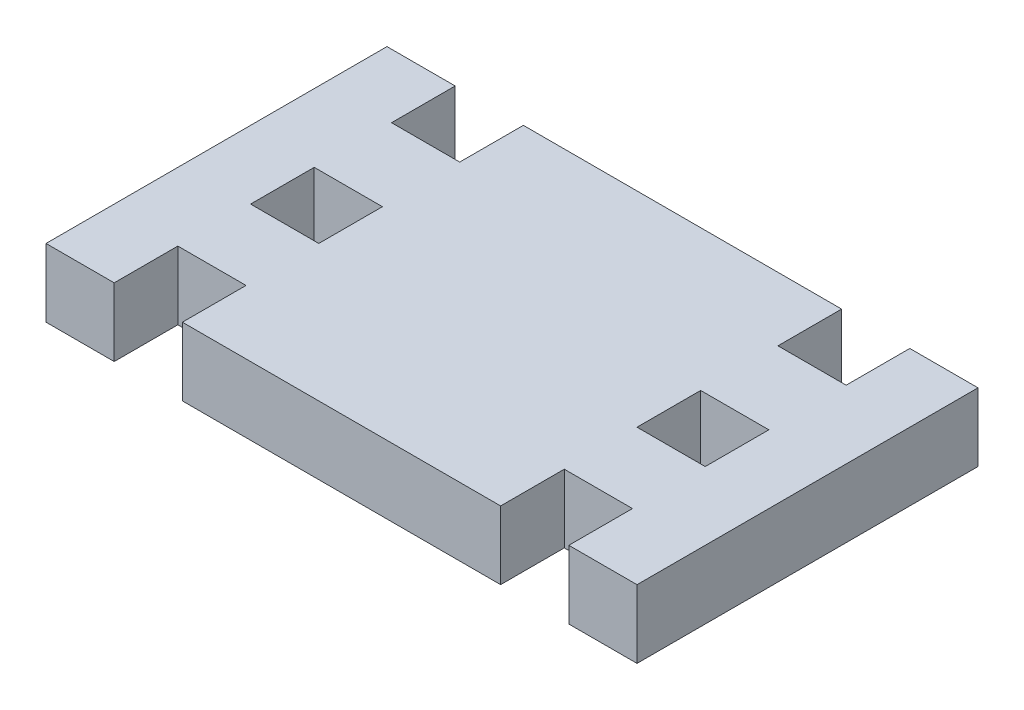
SolidWorks part; units mm, degrees
ref_plane "Front Plane" through (0, 0, 0) normal (0, 0, 1) x (1, 0, 0)
ref_plane "Top Plane" through (0, 0, 0) normal (0, 1, 0) x (1, 0, 0)
ref_plane "Right Plane" through (0, 0, 0) normal (1, 0, 0) x (0, 0, -1)
sketch "Sketch1" plane through (0, 0, 0) normal (0, 1, 0) x (1, 0, 0)
  line L0 (-10, -6.9776) -> (-7, -6.9776)
  line L5 (-7, -9.7776) -> (7, -9.7776)
  line L11 (-7, 5.2224) -> (7, 5.2224)
  line L30 (-7.5, -7.5) -> (7.5, 7.5) construction
  line L35 (-7.5, 7.5) -> (7.5, -7.5) construction
  line L45 (-10, 2.4224) -> (-7, 2.4224)
  line L46 (-7, 5.2224) -> (-7, 2.4224)
  line L48 (-7, -6.9776) -> (-7, -9.7776)
  line L50 (-10, -0.9776) -> (-7, -0.9776)
  line L52 (-10, -3.7776) -> (-7, -3.7776)
  line L53 (-7, -0.9776) -> (-7, -3.7776)
  line L54 (0, 5.2224) -> (0, -9.7776) construction
  line L55 (7, -0.9776) -> (7, -3.7776)
  line L56 (10, -3.7776) -> (7, -3.7776)
  line L57 (10, -0.9776) -> (7, -0.9776)
  line L59 (7, -6.9776) -> (7, -9.7776)
  line L60 (7, 5.2224) -> (7, 2.4224)
  line L61 (10, 2.4224) -> (7, 2.4224)
  line L63 (10, -6.9776) -> (7, -6.9776)
  line L64 (10, -0.9776) -> (10, -3.7776)
  line L65 (10, 5.2224) -> (13, 5.2224)
  line L66 (10, 5.2224) -> (10, 2.4224)
  line L67 (10, -9.7776) -> (13, -9.7776)
  line L68 (13, 5.2224) -> (13, -9.7776)
  line L69 (10, -6.9776) -> (10, -9.7776)
  line L70 (-10, -0.9776) -> (-10, -3.7776)
  line L71 (-13, 5.2224) -> (-10, 5.2224)
  line L72 (-13, 5.2224) -> (-13, -9.7776)
  line L73 (-13, -9.7776) -> (-10, -9.7776)
  line L74 (-10, 5.2224) -> (-10, 2.4224)
  line L75 (-10, -6.9776) -> (-10, -9.7776)
  point P0 (0, 0)
  dimension "D3" = 3
  dimension "D1" = 15
  dimension "D2" = 3
  dimension "D4" = 2.8
  dimension "D5" = 2.8
  dimension "D6" = 14
  dimension "D7" = 3
  dimension "D8" = 2.8
  dimension "D9" = 3.4
  dimension "D10" = 15
  dimension "D11" = 0
  dimension "D12" = 3
  dimension "D13" = 15
  dimension "D14" = 0
extrude "Boss-Extrude1" add sketch "Sketch1" along normal blind 3
